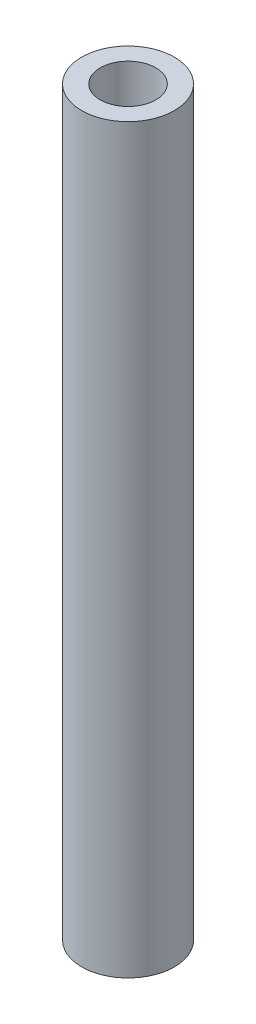
SolidWorks part; units mm, degrees
ref_plane "前视基准面" through (0, 0, 0) normal (0, 0, 1) x (1, 0, 0)
ref_plane "上视基准面" through (0, 0, 0) normal (0, 1, 0) x (1, 0, 0)
ref_plane "右视基准面" through (0, 0, 0) normal (1, 0, 0) x (0, 0, -1)
sketch "草图1" plane through (0, 0, 0) normal (0, 1, 0) x (1, 0, 0)
  circle A0 centre (0, 0) radius 1.5
  dimension "D1" = 3
extrude "拉伸-薄壁1" add sketch "草图1" along normal blind 40 thin
